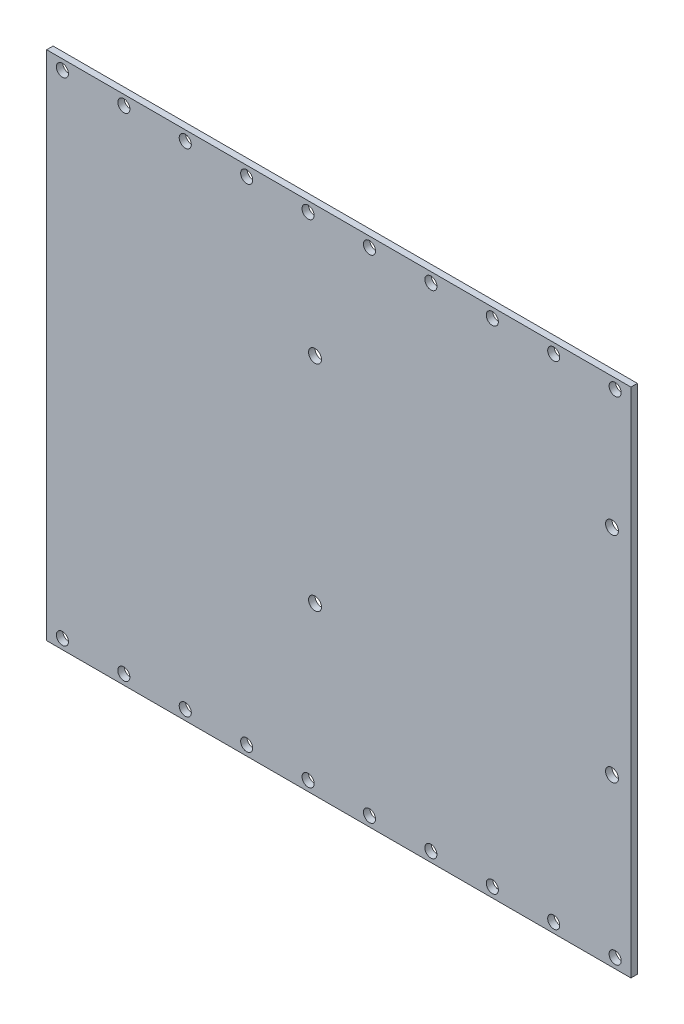
SolidWorks part; units mm, degrees
material "Fibre de verre A"
ref_plane "Plan de face" through (0, 0, 0) normal (0, 0, 1) x (1, 0, 0)
ref_plane "Plan de dessus" through (0, 0, 0) normal (0, 1, 0) x (1, 0, 0)
ref_plane "Plan de droite" through (0, 0, 0) normal (1, 0, 0) x (0, 0, -1)
sketch "Esquisse1" plane through (0, 0, 0) normal (0, 0, 1) x (1, 0, 0)
  line L1 (-72.5, 63.5) -> (72.5, 63.5)
  line L2 (-72.5, 63.5) -> (-72.5, -63.5)
  line L3 (-72.5, -63.5) -> (72.5, -63.5)
  line L4 (72.5, 63.5) -> (72.5, -63.5)
  line L5 (-72.5, 63.5) -> (72.5, -63.5) construction
  line L6 (-72.5, -63.5) -> (72.5, 63.5) construction
  point P0 (0, 0)
  dimension "D1" = 127
  dimension "D2" = 145
extrude "Boss.-Extru.1" add sketch "Esquisse1" along normal blind 1.6
hole_wizard "Diamètre du perçage Ø3.0 (3)1" positions "Esquisse3" profile "Esquisse2" hole size "Ø3.0" standard "Iso" end condition through all
sketch "Esquisse3" plane through (0, 0, 0) normal (0, 0, -1) x (-1, 0, 0)
  point P0 (-68.58, 61.05)
  point P9 (-38.1, 61.05)
  point P18 (-7.62, 61.05)
  point P27 (22.86, 61.05)
  point P36 (53.34, 61.05)
  point P42 (68.58, 61.05)
  point P45 (-68.58, -61.05)
  point P48 (-53.34, -61.05)
  point P51 (-38.1, -61.05)
  point P54 (-22.86, -61.05)
  point P57 (-7.62, -61.05)
  point P60 (7.62, -61.05)
  point P63 (22.86, -61.05)
  point P66 (38.1, -61.05)
  point P69 (53.34, -61.05)
  point P72 (68.58, -61.05)
  point P75 (38.1, 61.05)
  point P78 (7.62, 61.05)
  point P81 (-22.86, 61.05)
  point P84 (-53.34, 61.05)
sketch "Esquisse2" plane through (68.58, 61.05, 0) normal (1, 0, 0) x (0, 1, 0)
  line L0 (0, 0) -> (0, 1.6)
  line L1 (0, 1.6) -> (1.5, 1.6)
  line L2 (1.5, 1.6) -> (1.5, 0)
  line L5 (1.5, 0) -> (0, 0)
  line L11 (0, -6.35) -> (0, 107.95) construction
  dimension "Diamètre du perçage jusqu'au prochain" = 3
  dimension "Profondeur du perçage jusqu'au prochain" = 1.6
sketch "Esquisse4" plane through (0, 0, 1.6) normal (0, 0, 1) x (1, 0, 0)
  line L1 (-72.5, -63.5) -> (72.5, -63.5) construction
  line L2 (72.5, -63.5) -> (72.5, 63.5) construction
  circle A0 centre (67.8, -22.2) radius 1.6
  circle A1 centre (-5.9, -22.2) radius 1.6
  circle A2 centre (-5.9, 31) radius 1.6
  circle A3 centre (67.8, 31) radius 1.6
  dimension "D1" = 3.2
  dimension "D2" = 3.2
  dimension "D3" = 3.2
  dimension "D8" = 3.2
  dimension "D4" = 4.7
  dimension "D5" = 73.7
  dimension "D6" = 53.2
  dimension "D7" = 41.3
  dimension "D9" = 53.2
  dimension "D10" = 73.7
extrude "Enlèv. mat.-Extru.1" cut sketch "Esquisse4" against normal up to next
